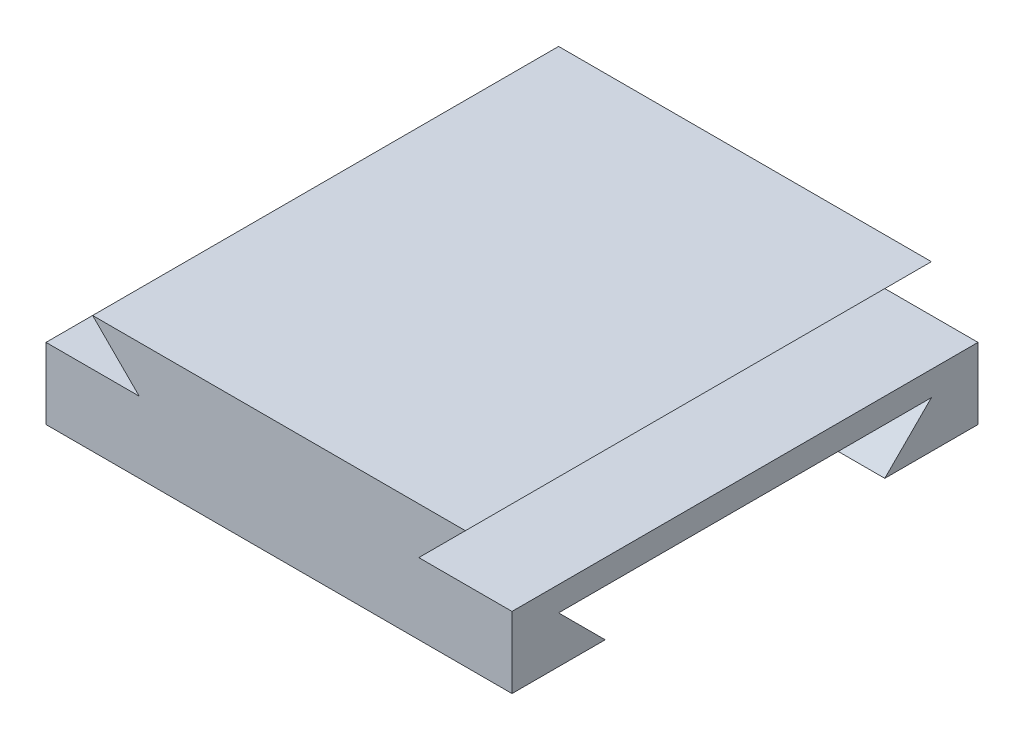
SolidWorks part; units mm, degrees
material "Aleación 1060"
ref_plane "Alzado" through (0, 0, 0) normal (0, 0, 1) x (1, 0, 0)
ref_plane "Planta" through (0, 0, 0) normal (0, 1, 0) x (1, 0, 0)
ref_plane "Vista lateral" through (0, 0, 0) normal (1, 0, 0) x (0, 0, -1)
sketch "Croquis1" plane through (0, 0, 0) normal (1, 0, 0) x (0, 0, -1)
  line L0 (-30, 3.5) -> (-40, 13.5)
  line L1 (50, -3.5) -> (-50, -3.5) construction
  line L2 (50, -3.5) -> (50, 3.5) construction
  line L3 (50, 3.5) -> (-50, 3.5) construction
  line L4 (-50, -3.5) -> (-50, 3.5) construction
  line L5 (50, -3.5) -> (-50, 3.5) construction
  line L6 (50, 3.5) -> (-50, -3.5) construction
  line L7 (-40, 13.5) -> (40, 13.5)
  line L8 (40, 13.5) -> (30, 3.5)
  line L9 (30, 3.5) -> (-30, 3.5) construction
  line L10 (-30, 3.5) -> (-50, 3.5)
  line L11 (-50, 3.5) -> (-50, 18.7709)
  line L12 (-50, 18.7709) -> (50, 18.7709)
  line L13 (50, 18.7709) -> (50, 3.5)
  line L14 (50, 3.5) -> (30, 3.5)
  point P0 (0, 0)
  dimension "D1" = 100
  dimension "D2" = 7
  dimension "D3" = 45
  dimension "D4" = 20
  dimension "D5" = 20
  dimension "D6" = 10
extrude "Saliente-Extruir1" add sketch "Croquis1" along normal blind 100
sketch "Croquis2" plane through (0, 0, -50) normal (0, 0, -1) x (-1, 0, 0)
  line L0 (-80, 18.7709) -> (-90, 28.7709)
  line L1 (-100, 18.7709) -> (0, 18.7709) construction
  line L2 (-90, 28.7709) -> (-10, 28.7709)
  line L3 (-10, 28.7709) -> (-20, 18.7709)
  line L4 (-20, 18.7709) -> (-80, 18.7709)
  dimension "D1" = 20
  dimension "D2" = 45
  dimension "D3" = 20
  dimension "D4" = 10
extrude "Saliente-Extruir2" add sketch "Croquis2" against normal blind 100
